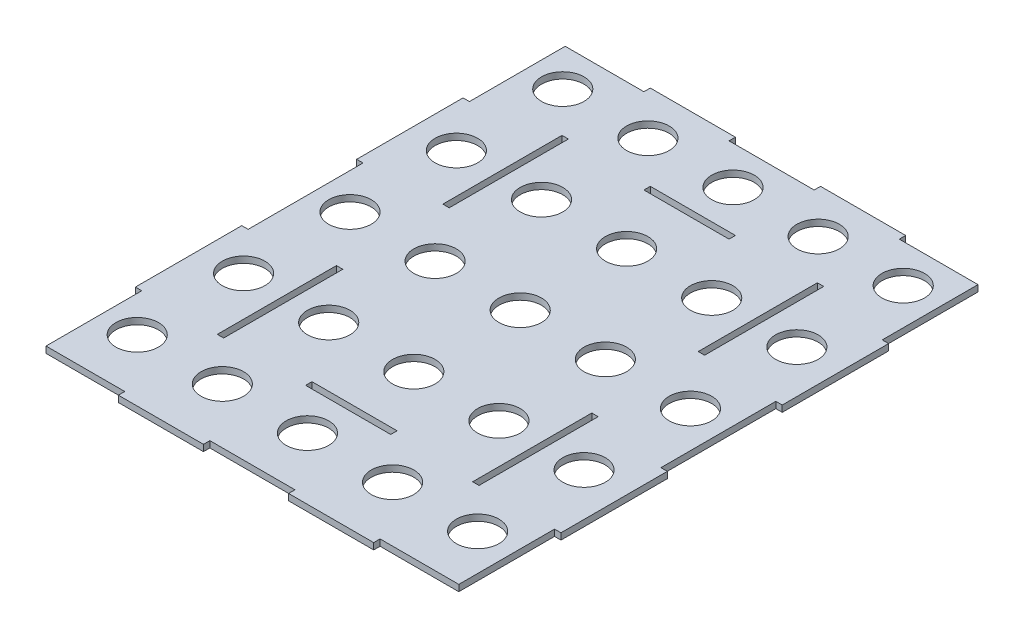
SolidWorks part; units mm, degrees
material "Acrylic (Medium-high impact)"
ref_plane "Alzado" through (0, 0, 0) normal (0, 0, 1) x (1, 0, 0)
ref_plane "Planta" through (0, 0, 0) normal (0, 1, 0) x (1, 0, 0)
ref_plane "Vista lateral" through (0, 0, 0) normal (1, 0, 0) x (0, 0, -1)
sketch "Sketch1" plane through (0, 0, 0) normal (0, 1, 0) x (1, 0, 0)
  line L0 (15.8384, 121) -> (55.8384, 121)
  line L1 (-64.1616, 121) -> (-24.1616, 121)
  line L3 (-64.1616, -129) -> (-24.1616, -129)
  line L4 (95.8384, 73) -> (95.8384, 23)
  line L5 (92.8384, -81) -> (-101.1616, -81) construction
  line L6 (-104.1616, -31) -> (-104.1616, -81)
  line L7 (-101.1616, 118) -> (-64.1616, 118)
  line L8 (-64.1616, 118) -> (-64.1616, 121)
  line L10 (-24.1616, 121) -> (-24.1616, 118)
  line L11 (-24.1616, 118) -> (15.8384, 118)
  line L12 (15.8384, 118) -> (15.8384, 121)
  line L14 (55.8384, 121) -> (55.8384, 118)
  line L15 (55.8384, 118) -> (92.8384, 118)
  line L16 (-101.1616, 73) -> (-101.1616, 118)
  line L17 (55.8384, -126) -> (92.8384, -126)
  line L18 (55.8384, -129) -> (55.8384, -126)
  line L19 (15.8384, -129) -> (55.8384, -129)
  line L20 (15.8384, -126) -> (15.8384, -129)
  line L21 (-24.1616, -126) -> (15.8384, -126)
  line L22 (-24.1616, -129) -> (-24.1616, -126)
  line L24 (-64.1616, -126) -> (-64.1616, -129)
  line L25 (-101.1616, -126) -> (-64.1616, -126)
  line L29 (-104.1616, 73) -> (-101.1616, 73)
  line L30 (92.8384, -126) -> (92.8384, -81)
  line L31 (92.8384, -81) -> (95.8384, -81)
  line L32 (95.8384, -81) -> (95.8384, -31)
  line L33 (95.8384, -31) -> (92.8384, -31)
  line L34 (92.8384, -31) -> (92.8384, 23)
  line L35 (92.8384, 23) -> (95.8384, 23)
  line L37 (95.8384, 73) -> (92.8384, 73)
  line L38 (92.8384, 73) -> (92.8384, 118)
  line L40 (-104.1616, 23) -> (-104.1616, 73)
  line L41 (-101.1616, 23) -> (-104.1616, 23)
  line L42 (-101.1616, -31) -> (-101.1616, 23)
  line L43 (-104.1616, -31) -> (-101.1616, -31)
  line L45 (-101.1616, -81) -> (-104.1616, -81)
  line L46 (-101.1616, -126) -> (-101.1616, -81)
  point P16 (-44.1616, -129)
  dimension "D1" = 3
  dimension "D2" = 45
  dimension "D3" = 40
  dimension "D4" = 3
  dimension "D5" = 3
  dimension "D6" = 3
  dimension "D7" = 3
  dimension "D8" = 40
  dimension "D9" = 3
  dimension "D10" = 3
  dimension "D11" = 50
  dimension "D12" = 54
  dimension "D13" = 3
  dimension "D14" = 250
  dimension "D15" = 50
  dimension "D16" = 3
  dimension "D17" = 3
  dimension "D18" = 40
  dimension "D19" = 3
  dimension "D20" = 45
  dimension "D21" = 3
  dimension "D22" = 200
  dimension "D23" = 3
  dimension "D24" = 40
  dimension "D25" = 40
  dimension "D26" = 40
  dimension "D27" = 45
  dimension "D28" = 40
  dimension "D29" = 40
  dimension "D30" = 50
  dimension "D31" = 45
  dimension "D32" = 50
extrude "Boss-Extrude1" add sketch "Sketch1" along normal blind 3
sketch "Sketch2" plane through (0, 3, 0) normal (0, 1, 0) x (1, 0, 0)
  line L0 (-64.1616, 118) -> (-64.1616, -126) construction
  line L1 (-24.1616, -126) -> (-24.1616, 118) construction
  line L2 (15.8384, 118) -> (15.8384, -126) construction
  line L3 (55.8384, -126) -> (55.8384, 118) construction
  line L4 (-65.6616, -25) -> (-62.6616, -25)
  line L5 (-124.5935, 0) -> (115.9924, 0) construction
  line L6 (-4.1616, -139.0118) -> (-4.1616, 138.172) construction
  line L7 (-65.6616, 25) -> (-65.6616, 81)
  line L8 (54.3384, 81) -> (57.3384, 81)
  line L11 (-62.6616, -25) -> (-62.6616, -81)
  line L12 (-65.6616, -25) -> (-65.6616, -81)
  line L13 (-65.6616, -81) -> (-62.6616, -81)
  line L14 (57.3384, 25) -> (57.3384, 81)
  line L15 (-64.1616, 25) -> (-62.6616, 25)
  line L16 (-64.1616, 25) -> (-65.6616, 25)
  line L18 (-62.6616, 25) -> (-62.6616, 81)
  line L19 (-62.6616, 81) -> (-65.6616, 81)
  line L20 (55.8384, 25) -> (57.3384, 25)
  line L44 (55.8384, 25) -> (54.3384, 25)
  line L45 (54.3384, 25) -> (54.3384, 81)
  line L46 (57.3384, -25) -> (54.3384, -25)
  line L47 (57.3384, -81) -> (54.3384, -81)
  line L48 (54.3384, -25) -> (54.3384, -81)
  line L49 (57.3384, -25) -> (57.3384, -81)
  line L50 (-62.6616, 81) -> (-24.1616, 81) construction
  line L51 (-24.1616, 81) -> (-24.1616, 78)
  line L52 (-24.1616, 78) -> (15.8384, 78)
  line L53 (15.8384, 78) -> (15.8384, 81)
  line L54 (15.8384, 81) -> (-24.1616, 81)
  line L55 (15.8384, -78) -> (15.8384, -81)
  line L56 (15.8384, -81) -> (-24.1616, -81)
  line L57 (-24.1616, -81) -> (-24.1616, -78)
  line L58 (-24.1616, -78) -> (15.8384, -78)
  line L59 (-84.3005, -40) -> (-84.3005, -10) construction
  line L60 (-84.3005, -25) -> (-48.3257, -25) construction
  circle A25 centre (-4.3005, 0) radius 10
  circle A26 centre (35.6995, 0) radius 10
  circle A27 centre (75.6995, 0) radius 10
  circle A28 centre (-44.3005, 0) radius 10
  circle A29 centre (-84.3005, 0) radius 10
  circle A30 centre (-84.3005, 50) radius 10
  circle A31 centre (-44.3005, 50) radius 10
  circle A32 centre (-4.3005, 50) radius 10
  circle A33 centre (35.6995, 50) radius 10
  circle A34 centre (75.6995, 50) radius 10
  circle A35 centre (-84.3005, 100) radius 10
  circle A36 centre (-44.3005, 100) radius 10
  circle A37 centre (-4.3005, 100) radius 10
  circle A38 centre (35.6995, 100) radius 10
  circle A39 centre (75.6995, 100) radius 10
  circle A40 centre (-84.3005, -50) radius 10
  circle A41 centre (-44.3005, -50) radius 10
  circle A42 centre (-4.3005, -50) radius 10
  circle A43 centre (35.6995, -50) radius 10
  circle A44 centre (75.6995, -50) radius 10
  circle A45 centre (-84.3005, -100) radius 10
  circle A46 centre (-44.3005, -100) radius 10
  circle A47 centre (-4.3005, -100) radius 10
  circle A48 centre (35.6995, -100) radius 10
  circle A49 centre (75.6995, -100) radius 10
  point P19 (-64.1616, -81)
  dimension "D1" = 3
  dimension "D5" = 3
  dimension "D6" = 3
  dimension "D7" = 1.5
  dimension "D8" = 3
  dimension "D10" = 25
  dimension "D11" = 25
  dimension "D2" = 3
  dimension "D3" = 3
  dimension "D4" = 3
extrude "Cut-Extrude1" cut sketch "Sketch2" against normal through all
